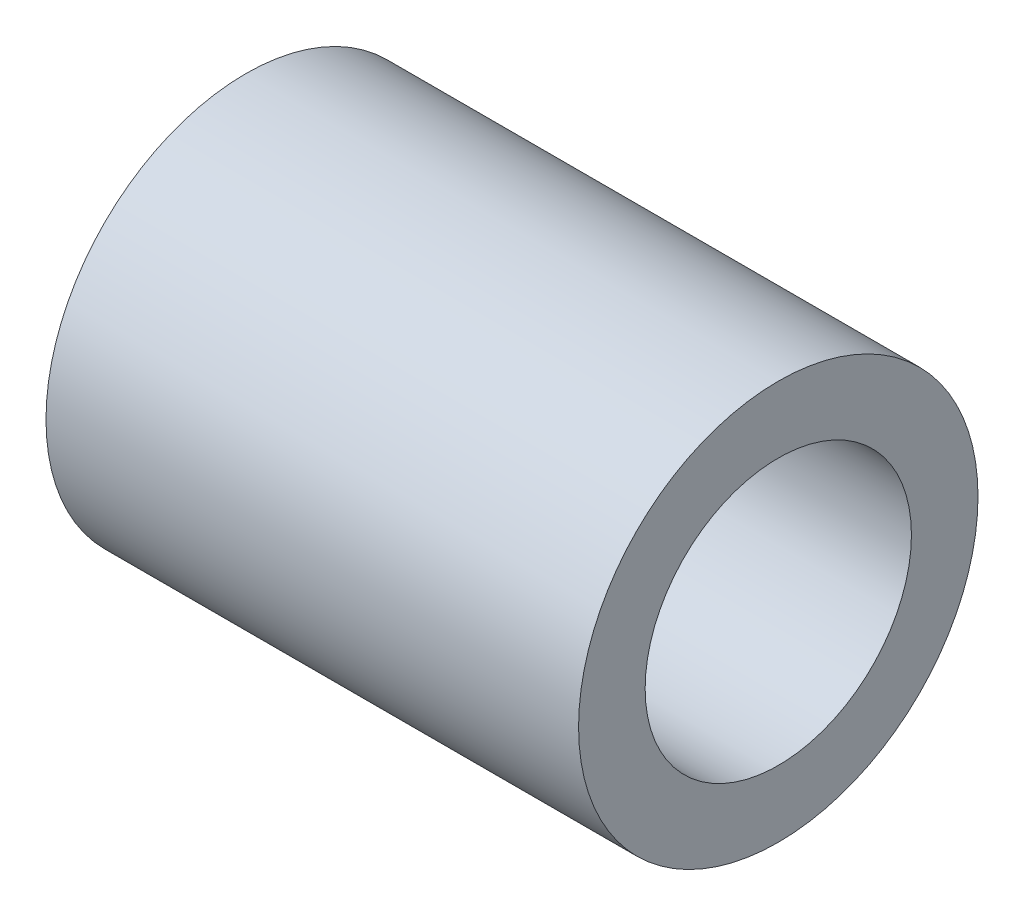
SolidWorks part; units mm, degrees
material "6061 Alloy"
ref_plane "Front Plane" through (0, 0, 0) normal (0, 0, 1) x (1, 0, 0)
ref_plane "Top Plane" through (0, 0, 0) normal (0, 1, 0) x (1, 0, 0)
ref_plane "Right Plane" through (0, 0, 0) normal (1, 0, 0) x (0, 0, -1)
sketch "Sketch1" plane through (0, 0, 0) normal (1, 0, 0) x (0, 0, -1)
  circle A0 centre (0, 0) radius 2.3813
  circle A1 centre (0, 0) radius 3.5719
  dimension "D1" = 4.7625
  dimension "D2" = 7.1437
extrude "Boss-Extrude1" add sketch "Sketch1" along normal mid plane 9.525
